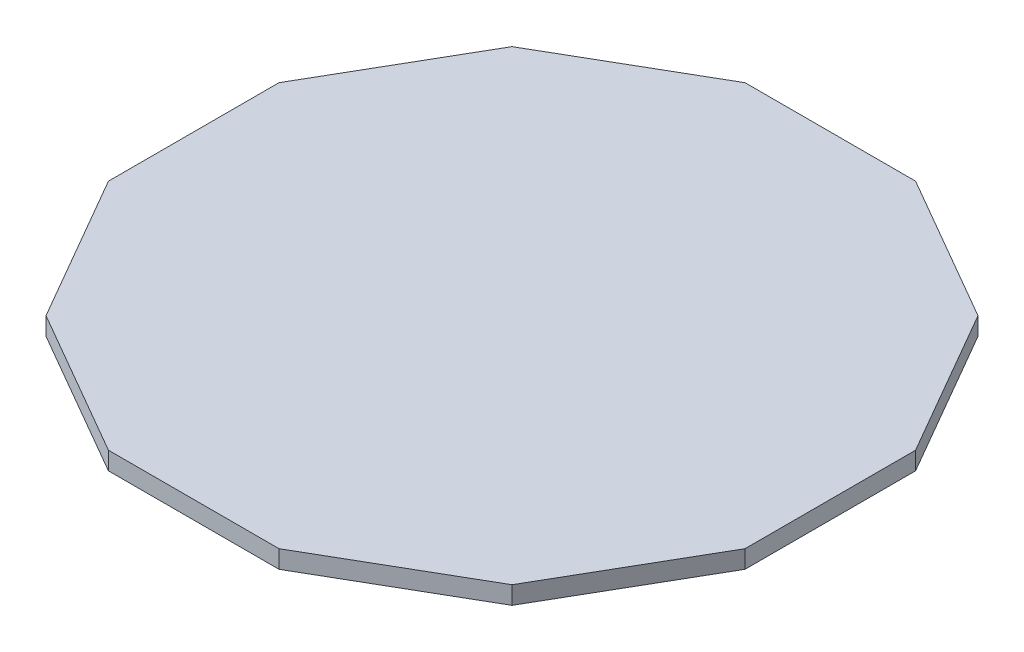
SolidWorks part; units mm, degrees
material "ABS PC"
ref_plane "Front Plane" through (0, 0, 0) normal (0, 0, 1) x (1, 0, 0)
ref_plane "Top Plane" through (0, 0, 0) normal (0, 1, 0) x (1, 0, 0)
ref_plane "Right Plane" through (0, 0, 0) normal (1, 0, 0) x (0, 0, -1)
sketch "Sketch1" plane through (0, 0, 0) normal (0, 1, 0) x (1, 0, 0)
  line L0 (13.148, 49.069) -> (-13.148, 49.069)
  line L1 (-13.148, 49.069) -> (-35.921, 35.921)
  line L2 (-35.921, 35.921) -> (-49.069, 13.148)
  line L3 (-49.069, 13.148) -> (-49.069, -13.148)
  line L4 (-49.069, -13.148) -> (-35.921, -35.921)
  line L5 (-35.921, -35.921) -> (-13.148, -49.069)
  line L6 (-13.148, -49.069) -> (13.148, -49.069)
  line L7 (13.148, -49.069) -> (35.921, -35.921)
  line L8 (35.921, -35.921) -> (49.069, -13.148)
  line L9 (49.069, -13.148) -> (49.069, 13.148)
  line L10 (49.069, 13.148) -> (35.921, 35.921)
  line L11 (35.921, 35.921) -> (13.148, 49.069)
  circle A0 centre (0, 0) radius 50.8
  dimension "D1" = 101.6
extrude "Boss-Extrude1" add sketch "Sketch1" against normal blind 2.921 contours L10 L11 L0 L1 L2 L3 L4 L5 L6 L7 L8 L9
sketch "Sketch2" plane through (0, 0, 0) normal (0, 1, 0) x (1, 0, 0)
  line L24 (51.99, 13.9307) -> (38.0593, 38.0593)
  line L25 (38.0593, 38.0593) -> (13.9307, 51.99)
  line L26 (13.9307, 51.99) -> (-13.9307, 51.99)
  line L27 (-13.9307, 51.99) -> (-38.0593, 38.0593)
  line L28 (-38.0593, 38.0593) -> (-51.99, 13.9307)
  line L29 (-51.99, 13.9307) -> (-51.99, -13.9307)
  line L30 (-51.99, -13.9307) -> (-38.0593, -38.0593)
  line L31 (-38.0593, -38.0593) -> (-13.9307, -51.99)
  line L32 (-13.9307, -51.99) -> (13.9307, -51.99)
  line L33 (13.9307, -51.99) -> (38.0593, -38.0593)
  line L34 (38.0593, -38.0593) -> (51.99, -13.9307)
  line L35 (51.99, -13.9307) -> (51.99, 13.9307)
  line L36 (51.99, 13.9307) -> (38.0593, 38.0593)
  line L37 (38.0593, 38.0593) -> (13.9307, 51.99)
  line L38 (13.9307, 51.99) -> (-13.9307, 51.99)
  line L39 (-13.9307, 51.99) -> (-38.0593, 38.0593)
  line L40 (-38.0593, 38.0593) -> (-51.99, 13.9307)
  line L41 (-51.99, 13.9307) -> (-51.99, -13.9307)
  line L42 (-51.99, -13.9307) -> (-38.0593, -38.0593)
  line L43 (-38.0593, -38.0593) -> (-13.9307, -51.99)
  line L44 (-13.9307, -51.99) -> (13.9307, -51.99)
  line L45 (13.9307, -51.99) -> (38.0593, -38.0593)
  line L46 (38.0593, -38.0593) -> (51.99, -13.9307)
  line L47 (51.99, -13.9307) -> (51.99, 13.9307)
  line L60 (49.069, 13.148) -> (35.921, 35.921)
  line L61 (35.921, 35.921) -> (13.148, 49.069)
  line L62 (13.148, 49.069) -> (-13.148, 49.069)
  line L63 (-13.148, 49.069) -> (-35.921, 35.921)
  line L64 (-35.921, 35.921) -> (-49.069, 13.148)
  line L65 (-49.069, 13.148) -> (-49.069, -13.148)
  line L66 (-49.069, -13.148) -> (-35.921, -35.921)
  line L67 (-35.921, -35.921) -> (-13.148, -49.069)
  line L68 (-13.148, -49.069) -> (13.148, -49.069)
  line L69 (13.148, -49.069) -> (35.921, -35.921)
  line L70 (35.921, -35.921) -> (49.069, -13.148)
  line L71 (49.069, -13.148) -> (49.069, 13.148)
  line L72 (49.069, 13.148) -> (35.921, 35.921)
  line L73 (35.921, 35.921) -> (13.148, 49.069)
  line L74 (13.148, 49.069) -> (-13.148, 49.069)
  line L75 (-13.148, 49.069) -> (-35.921, 35.921)
  line L76 (-35.921, 35.921) -> (-49.069, 13.148)
  line L77 (-49.069, 13.148) -> (-49.069, -13.148)
  line L78 (-49.069, -13.148) -> (-35.921, -35.921)
  line L79 (-35.921, -35.921) -> (-13.148, -49.069)
  line L80 (-13.148, -49.069) -> (13.148, -49.069)
  line L81 (13.148, -49.069) -> (35.921, -35.921)
  line L82 (35.921, -35.921) -> (49.069, -13.148)
  line L83 (49.069, -13.148) -> (49.069, 13.148)
  dimension "D1" = 2.921
  dimension "D2" = 0
extrude "Boss-Extrude2" add sketch "Sketch2" against normal up to surface (2.921 mm away) up to face at (0, -2.921, 0)
